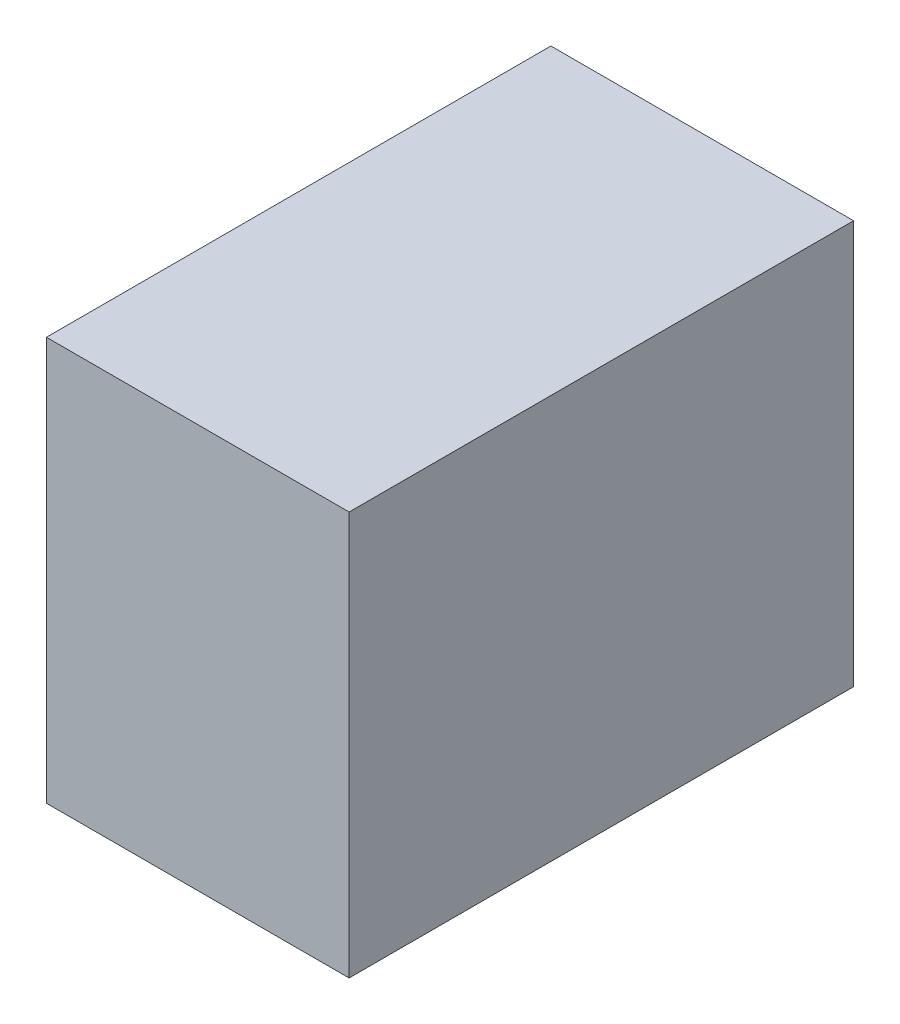
SolidWorks part; units mm, degrees
material "Low Carbon Steel"
ref_plane "Front Plane" through (0, 0, 0) normal (0, 0, 1) x (1, 0, 0)
ref_plane "Top Plane" through (0, 0, 0) normal (0, 1, 0) x (1, 0, 0)
ref_plane "Right Plane" through (0, 0, 0) normal (1, 0, 0) x (0, 0, -1)
sketch "Sketch1" plane through (0, 0, 0) normal (0, 0, 1) x (1, 0, 0)
  line L0 (-38.1, 50.8) -> (38.1, -50.8) construction
  line L1 (-38.1, 50.8) -> (38.1, 50.8)
  line L2 (-38.1, 50.8) -> (-38.1, -50.8)
  line L3 (-38.1, -50.8) -> (38.1, -50.8)
  line L4 (38.1, 50.8) -> (38.1, -50.8)
  dimension "D1" = 101.6
  dimension "D2" = 76.2
extrude "Boss-Extrude1" add sketch "Sketch1" along normal blind 127
other "Freeze***"
